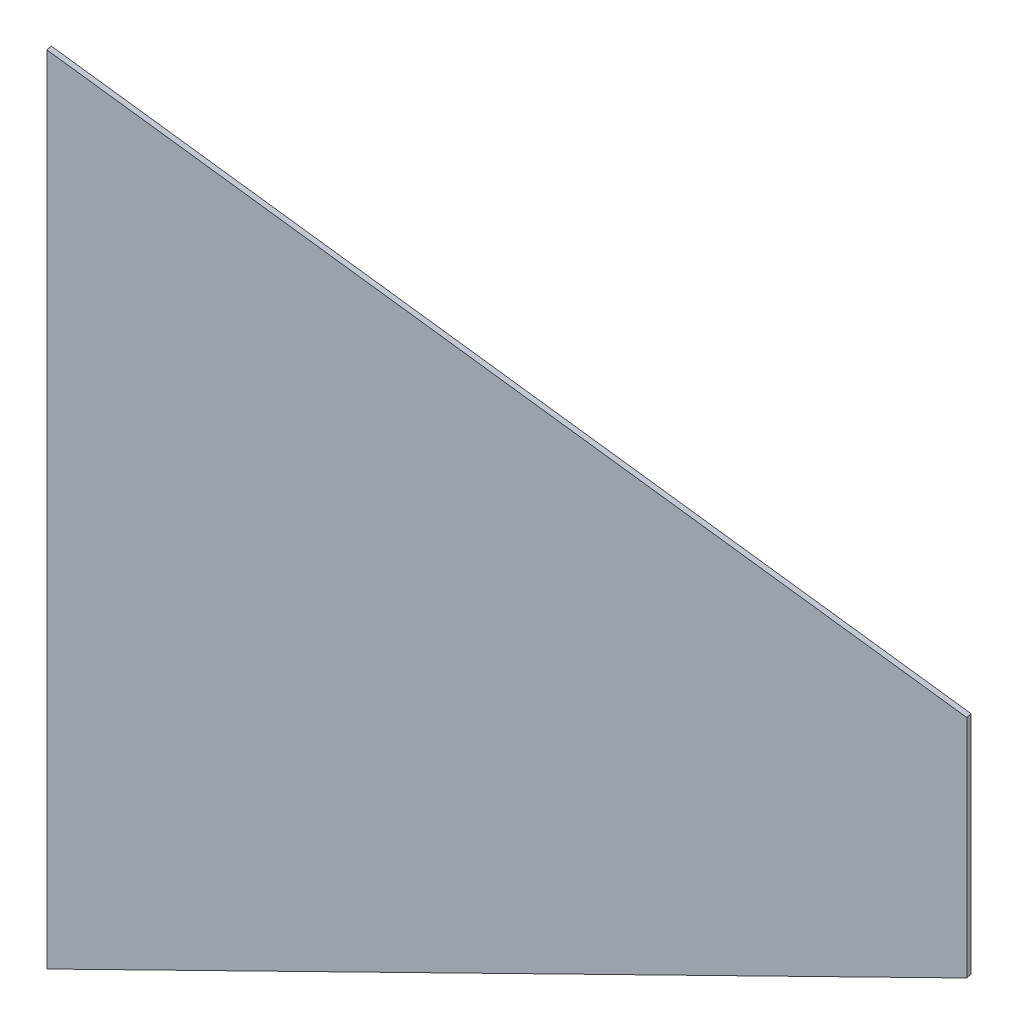
SolidWorks part; units mm, degrees
ref_plane "Front Plane" through (0, 0, 0) normal (0, 0, 1) x (1, 0, 0)
ref_plane "Top Plane" through (0, 0, 0) normal (0, 1, 0) x (1, 0, 0)
ref_plane "Right Plane" through (0, 0, 0) normal (1, 0, 0) x (0, 0, -1)
ref_plane "Plane1" through (161.0176, 0, 726.3033) normal (0.2164, 0, 0.9763) x (0, 1, 0)
sketch "Sketch1" plane through (161.0176, 0, 726.3033) normal (0.2164, 0, 0.9763) x (0, 1, 0)
  line L0 (-224.0987, 535.8712) -> (-25.9271, 0)
  line L1 (-25.9271, 0) -> (25.9271, 0)
  line L2 (25.9271, 0) -> (224.0987, 535.8712)
  line L3 (224.0987, 535.8712) -> (-224.0987, 535.8712)
  point P7 (0, 0)
  dimension "D1" = 571.3404
  dimension "D2" = 571.3404
  dimension "D3" = 51.8541
  dimension "D4" = 40.59
extrude "Boss-Extrude1" add sketch "Sketch1" against normal blind 3.175
sketch "Sketch2" plane through (161.0176, 0, 726.3033) normal (0.2164, 0, 0.9763) x (0.9763, 0, -0.2164)
  line L0 (-535.8712, -224.0987) -> (0, -25.927) construction
  line L1 (-101.6, -63.5) -> (0, -63.5)
  line L2 (-101.6, -63.5) -> (-101.6, 63.5)
  line L3 (-101.6, 63.5) -> (0, 63.5)
  line L4 (0, -63.5) -> (0, 63.5)
  line L5 (0, 25.9271) -> (-535.8712, 224.0987) construction
  line L6 (0, -25.9271) -> (0, 25.9271) construction
  dimension "D1" = 101.6
extrude "Cut-Extrude1" cut sketch "Sketch2" against normal through all both and the other way through all
